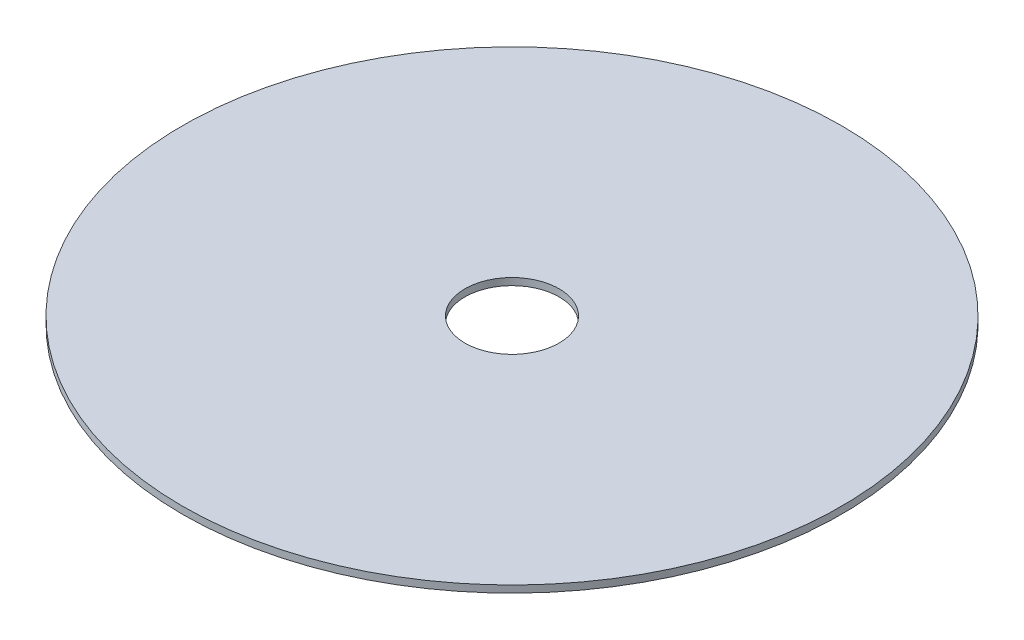
SolidWorks part; units mm, degrees
ref_plane "Front Plane" through (0, 0, 0) normal (0, 0, 1) x (1, 0, 0)
ref_plane "Top Plane" through (0, 0, 0) normal (0, 1, 0) x (1, 0, 0)
ref_plane "Right Plane" through (0, 0, 0) normal (1, 0, 0) x (0, 0, -1)
sketch "Sketch1" plane through (0, 0, 0) normal (0, 1, 0) x (1, 0, 0)
  circle A0 centre (0, 0) radius 140
  circle A1 centre (0, 0) radius 20
  dimension "D1" = 280
  dimension "D2" = 40
extrude "Boss-Extrude1" add sketch "Sketch1" along normal blind 3
